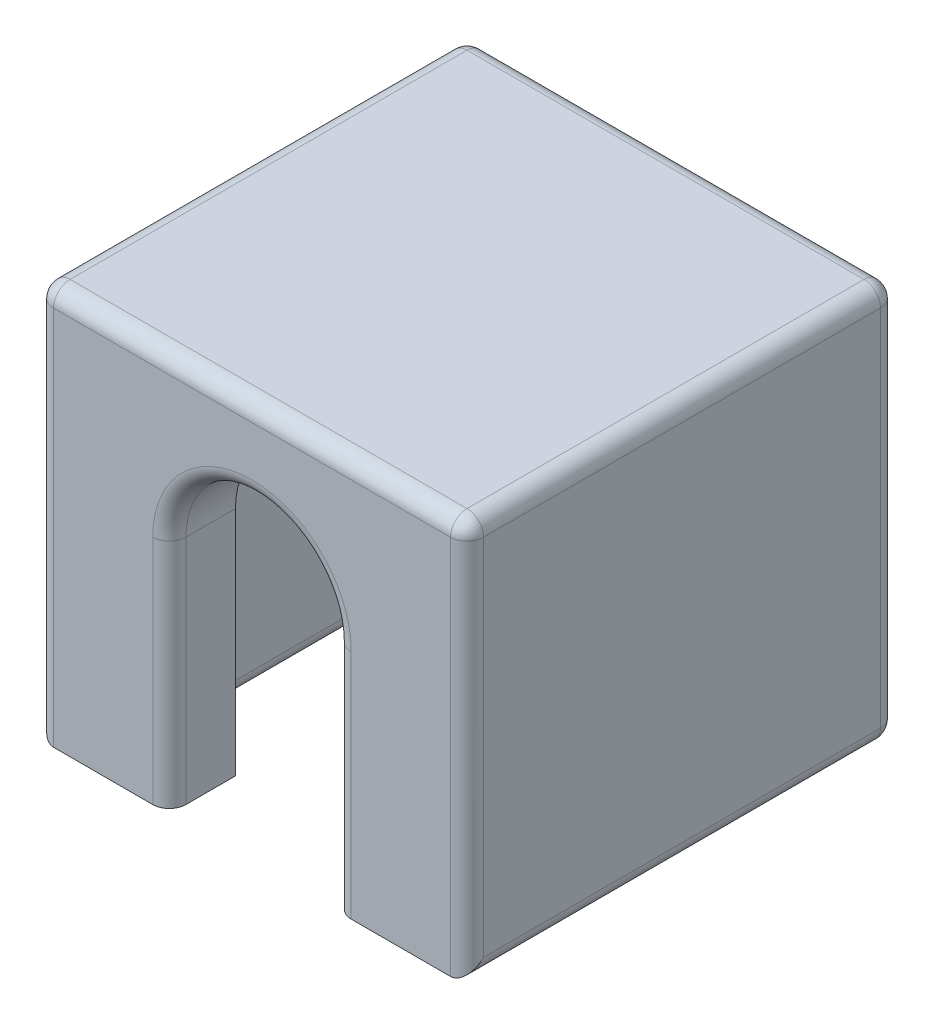
SolidWorks part; units mm, degrees
ref_plane "Front Plane" through (0, 0, 0) normal (0, 0, 1) x (1, 0, 0)
ref_plane "Top Plane" through (0, 0, 0) normal (0, 1, 0) x (1, 0, 0)
ref_plane "Right Plane" through (0, 0, 0) normal (1, 0, 0) x (0, 0, -1)
sketch "Sketch1" plane through (0, 0, 0) normal (0, 1, 0) x (1, 0, 0)
  line L9 (0, 0) -> (1981.2, 0)
  line L10 (0, 0) -> (0, 1981.2)
  line L11 (0, 1981.2) -> (1981.2, 1981.2)
  line L12 (1981.2, 0) -> (1981.2, 1981.2)
  dimension "D1" = 1981.2
  dimension "D2" = 1981.2
extrude "Boss-Extrude1" add sketch "Sketch1" along normal blind 1828.8
sketch "Sketch2" plane through (0, 0, 0) normal (0, 0, 1) x (1, 0, 0)
  line L0 (0, 0) -> (1981.2, 0) construction
  line L1 (609.6, 0) -> (1371.6, 0)
  line L2 (609.6, 0) -> (609.6, 1066.8)
  line L4 (1371.6, 0) -> (1371.6, 1066.8)
  line L5 (0, 1828.8) -> (0, 0) construction
  arc A0 (609.6, 1066.8) -> (1371.6, 1066.8) centre (990.6, 1066.8) cw
  dimension "D1" = 1066.8
  dimension "D2" = 609.6
  dimension "D3" = 762
extrude "Cut-Extrude1" cut sketch "Sketch2" against normal blind 1371.6
sketch "Sketch3" plane through (0, 1828.8, 0) normal (0, 1, 0) x (1, 0, 0)
  line L8 (304.8, 1676.4) -> (304.8, 304.8)
  line L9 (304.8, 304.8) -> (1676.4, 304.8)
  line L10 (1676.4, 304.8) -> (1676.4, 1676.4)
  line L11 (1676.4, 1676.4) -> (304.8, 1676.4)
  line L12 (304.8, 1676.4) -> (304.8, 304.8)
  line L13 (304.8, 304.8) -> (1676.4, 304.8)
  line L14 (1676.4, 304.8) -> (1676.4, 1676.4)
  line L15 (1676.4, 1676.4) -> (304.8, 1676.4)
  dimension "D1" = 304.8
extrude "Cut-Extrude2" cut sketch "Sketch3" against normal through all
sketch "Sketch4" plane through (0, 0, -1981.2) normal (0, 0, -1) x (-1, 0, 0)
  line L5 (-1295.4, 1219.2) -> (-685.8, 1219.2)
  line L6 (-1295.4, 1219.2) -> (-1295.4, 609.6)
  line L7 (-1295.4, 609.6) -> (-685.8, 609.6)
  line L8 (-685.8, 1219.2) -> (-685.8, 609.6)
  line L9 (-990.6, 1828.8) -> (-990.6, 0) construction
  line L11 (-1981.2, 1828.8) -> (0, 1828.8) construction
  line L12 (-1981.2, 0) -> (0, 0) construction
  line L13 (-990.6, 1219.2) -> (-990.6, 609.6) construction
  point P12 (-990.6, 914.4)
  point P13 (-990.6, 914.4)
  dimension "D1" = 609.6
extrude "Cut-Extrude3" cut sketch "Sketch4" against normal up to surface (304.8 mm away) contours L6 L5 L8 L7 up to face at (990.6, 914.4, -1676.4)
sketch "Sketch5" plane through (1981.2, 0, 0) normal (1, 0, 0) x (0, 0, -1)
  line L0 (1981.2, 1828.8) -> (1981.2, 0) construction
  line L1 (0, 1828.8) -> (1981.2, 1828.8)
  line L2 (0, 1828.8) -> (0, 1524)
  line L3 (0, 1524) -> (1981.2, 1524)
  line L4 (1981.2, 1828.8) -> (1981.2, 1524)
  dimension "D1" = 304.8
extrude "Boss-Extrude2" add sketch "Sketch5" against normal up to surface (1676.4 mm away) up to face at (304.8, 914.4, -990.6)
fillet "Fillet1" radius 76.2 28 edges at (1676.4, 0, -990.6) (304.8, 0, -990.6) (1371.6, 533.4, 0) (990.6, 1447.8, 0) (990.6, 1219.2, -1981.2) (1295.4, 914.4, -1981.2) (990.6, 609.6, -1981.2) (685.8, 914.4, -1981.2) (990.6, 0, -1981.2) (1981.2, 914.4, -1981.2) (990.6, 1828.8, -1981.2) (0, 914.4, -1981.2) (990.6, 609.6, -1676.4) (1295.4, 914.4, -1676.4) (990.6, 1219.2, -1676.4) (685.8, 914.4, -1676.4) (990.6, 0, -1676.4) (304.8, 762, -1676.4) (990.6, 1524, -1676.4) (1676.4, 762, -1676.4) (0, 0, -990.6) (0, 1828.8, -990.6) (609.6, 533.4, 0) (0, 914.4, 0) (1981.2, 0, -990.6) (1981.2, 914.4, 0) (990.6, 1828.8, 0) (1981.2, 1828.8, -990.6)
equation "\"2f\"=304.8"
